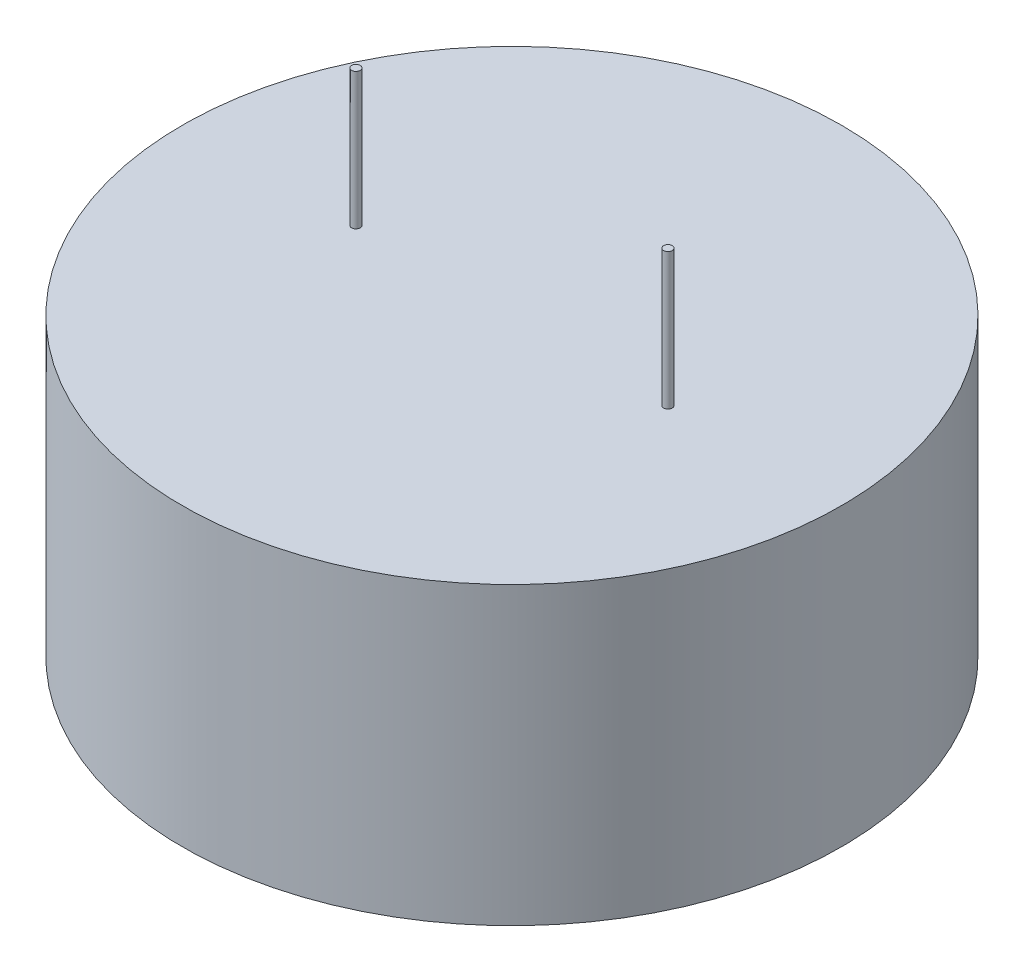
SolidWorks part; units mm, degrees
ref_plane "Plan de face" through (0, 0, 0) normal (0, 0, 1) x (1, 0, 0)
ref_plane "Plan de dessus" through (0, 0, 0) normal (0, 1, 0) x (1, 0, 0)
ref_plane "Plan de droite" through (0, 0, 0) normal (1, 0, 0) x (0, 0, -1)
sketch "Esquisse1" plane through (0, 0, 0) normal (0, 1, 0) x (1, 0, 0)
  circle A0 centre (0, 0) radius 14.5
  dimension "D1" = 29
extrude "Boss.-Extru.1" add sketch "Esquisse1" along normal blind 13
sketch "Esquisse2" plane through (0, 13, 0) normal (0, 1, 0) x (1, 0, 0)
  line L0 (0, 0) -> (0, 50000) construction
  circle A1 centre (-6.8649, 0) radius 0.19
extrude "Boss.-Extru.2" add sketch "Esquisse2" along normal blind 6
mirror "Symétrie1" about plane through (0, 0, 0) normal (1, 0, 0) of "Boss.-Extru.2"
